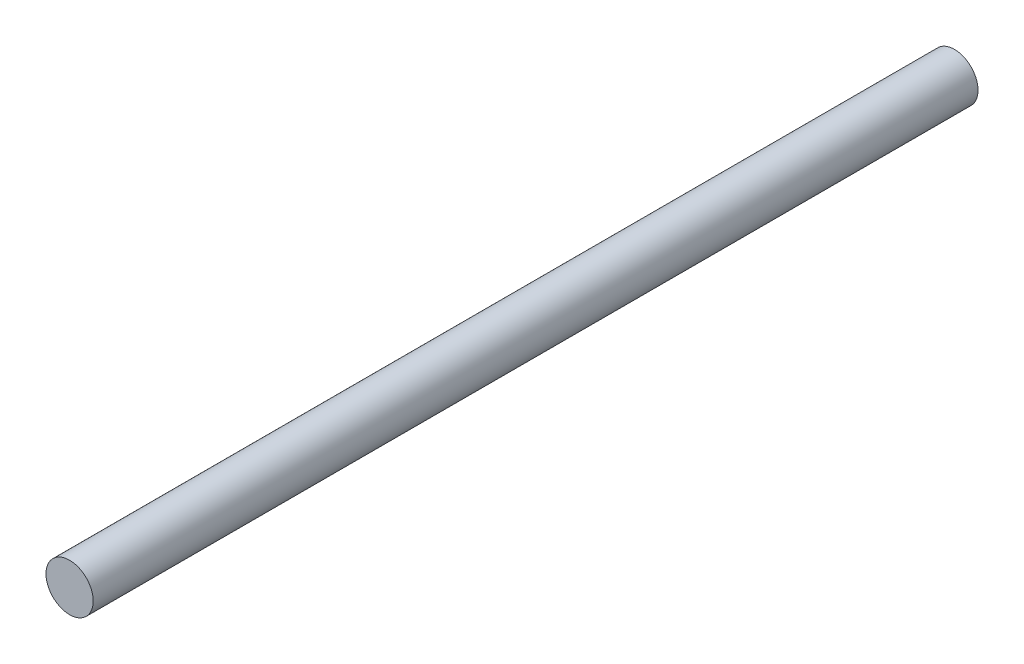
SolidWorks part; units mm, degrees
ref_plane "Front Plane" through (0, 0, 0) normal (0, 0, 1) x (1, 0, 0)
ref_plane "Top Plane" through (0, 0, 0) normal (0, 1, 0) x (1, 0, 0)
ref_plane "Right Plane" through (0, 0, 0) normal (1, 0, 0) x (0, 0, -1)
sketch "Sketch2" plane through (0, 0, -54) normal (0, 0, -1) x (-1, 0, 0)
  circle A0 centre (0, 0) radius 4
  dimension "D1" = 8
extrude "Boss-Extrude1" add sketch "Sketch2" along normal mid plane 150
